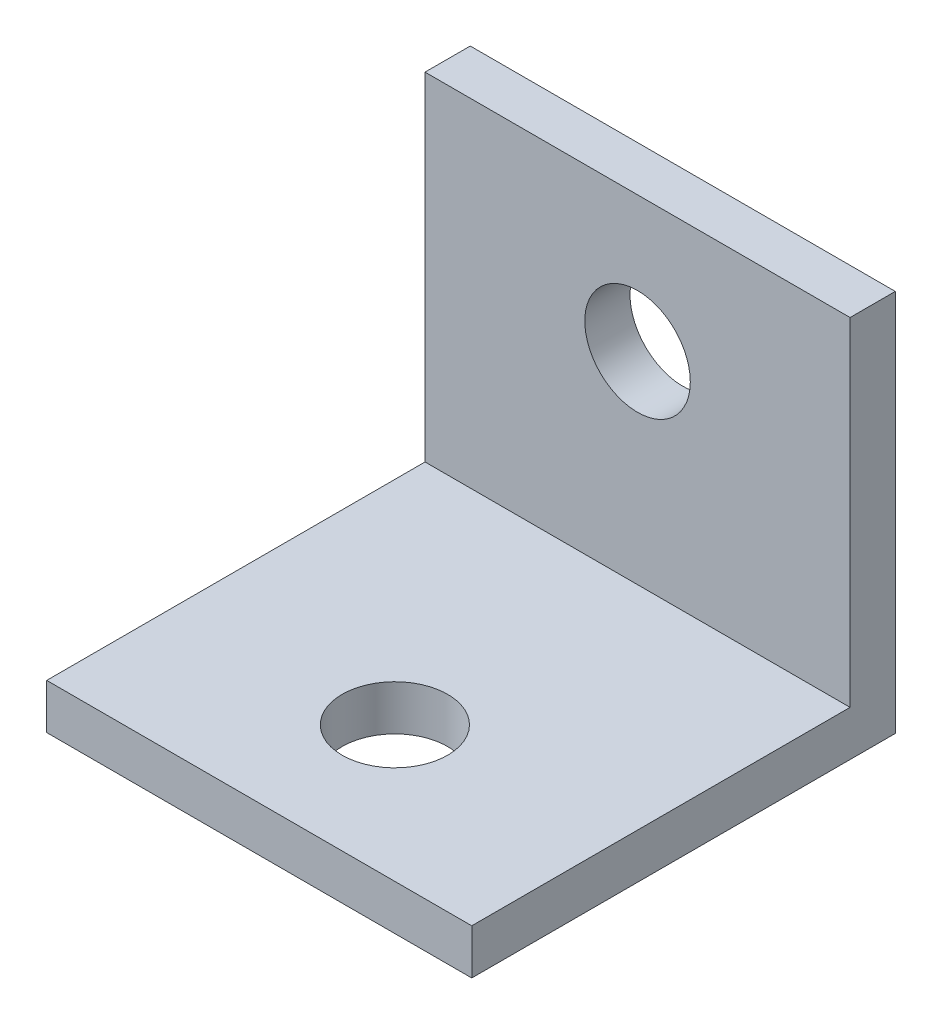
SolidWorks part; units mm, degrees
ref_plane "Plano frontal" through (0, 0, 0) normal (0, 0, 1) x (1, 0, 0)
ref_plane "Plano superior" through (0, 0, 0) normal (0, 1, 0) x (1, 0, 0)
ref_plane "Plano direito" through (0, 0, 0) normal (1, 0, 0) x (0, 0, -1)
sketch "Esboço1" plane through (0, 0, 0) normal (0, 0, 1) x (1, 0, 0)
  line L1 (-28.2, 16.1823) -> (0, 16.1823)
  line L2 (-28.2, 16.1823) -> (-28.2, -9.2177)
  line L3 (-28.2, -9.2177) -> (0, -9.2177)
  line L4 (0, 16.1823) -> (0, -9.2177)
  dimension "D1" = 25.4
  dimension "D2" = 28.2
extrude "Ressalto-extrusão1" add sketch "Esboço1" along normal blind 3
sketch "Esboço2" plane through (0, 0, 3) normal (0, 0, 1) x (1, 0, 0)
  line L0 (0, -9.2177) -> (0, 16.1823) construction
  line L1 (-28.2, -9.2177) -> (0, -9.2177)
  line L2 (-28.2, -9.2177) -> (-28.2, -6.2177)
  line L3 (-28.2, -6.2177) -> (0, -6.2177)
  line L4 (0, -9.2177) -> (0, -6.2177)
extrude "Ressalto-extrusão2" add sketch "Esboço2" along normal blind 25.1
sketch "Esboço3" plane through (0, -6.2177, 0) normal (0, 1, 0) x (1, 0, 0)
  line L0 (-14.1, -28.1) -> (-14.1, -19.1) construction
  line L1 (0, -28.1) -> (-28.2, -28.1) construction
  circle A0 centre (-14.1, -19.1) radius 3.5
  dimension "D1" = 7
extrude "Corte-extrusão1" cut sketch "Esboço3" against normal blind 3
sketch "Esboço4" plane through (0, 0, 3) normal (0, 0, 1) x (1, 0, 0)
  line L0 (-14.1, 16.1823) -> (-14.1, 7.1823) construction
  line L1 (0, 16.1823) -> (-28.2, 16.1823) construction
  circle A0 centre (-14.1, 7.1823) radius 3.5
  dimension "D1" = 7
extrude "Corte-extrusão2" cut sketch "Esboço4" against normal blind 3
